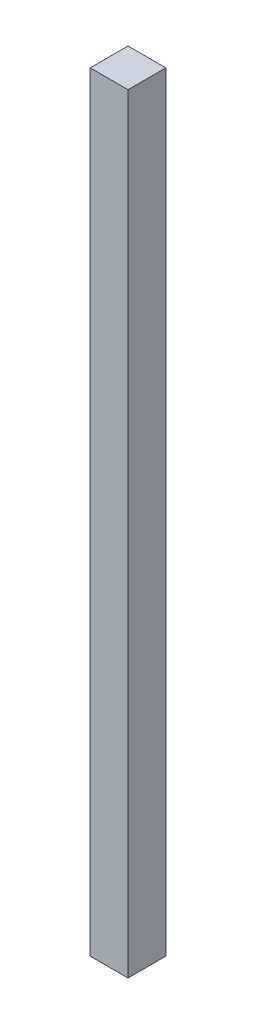
SolidWorks part; units mm, degrees
ref_plane "Front Plane" through (0, 0, 0) normal (0, 0, 1) x (1, 0, 0)
ref_plane "Top Plane" through (0, 0, 0) normal (0, 1, 0) x (1, 0, 0)
ref_plane "Right Plane" through (0, 0, 0) normal (1, 0, 0) x (0, 0, -1)
sketch "Sketch1" plane through (0, 0, 0) normal (0, 1, 0) x (1, 0, 0)
  line L1 (-7.5, -7.5) -> (7.5, -7.5)
  line L2 (-7.5, -7.5) -> (-7.5, 7.5)
  line L3 (-7.5, 7.5) -> (7.5, 7.5)
  line L4 (7.5, -7.5) -> (7.5, 7.5)
  line L5 (-7.5, -7.5) -> (7.5, 7.5) construction
  line L6 (-7.5, 7.5) -> (7.5, -7.5) construction
  point P0 (0, 0)
  dimension "D1" = 15
extrude "Boss-Extrude1" add sketch "Sketch1" along normal blind 304.8
sketch "Sketch3" plane through (7.5, 0, 0) normal (1, 0, 0) x (0, 0, -1)
  line L0 (-7.5, 304.8) -> (7.5, 304.8) construction
  circle A0 centre (0, 152.4) radius 6.4055
  dimension "D1" = 152.4
